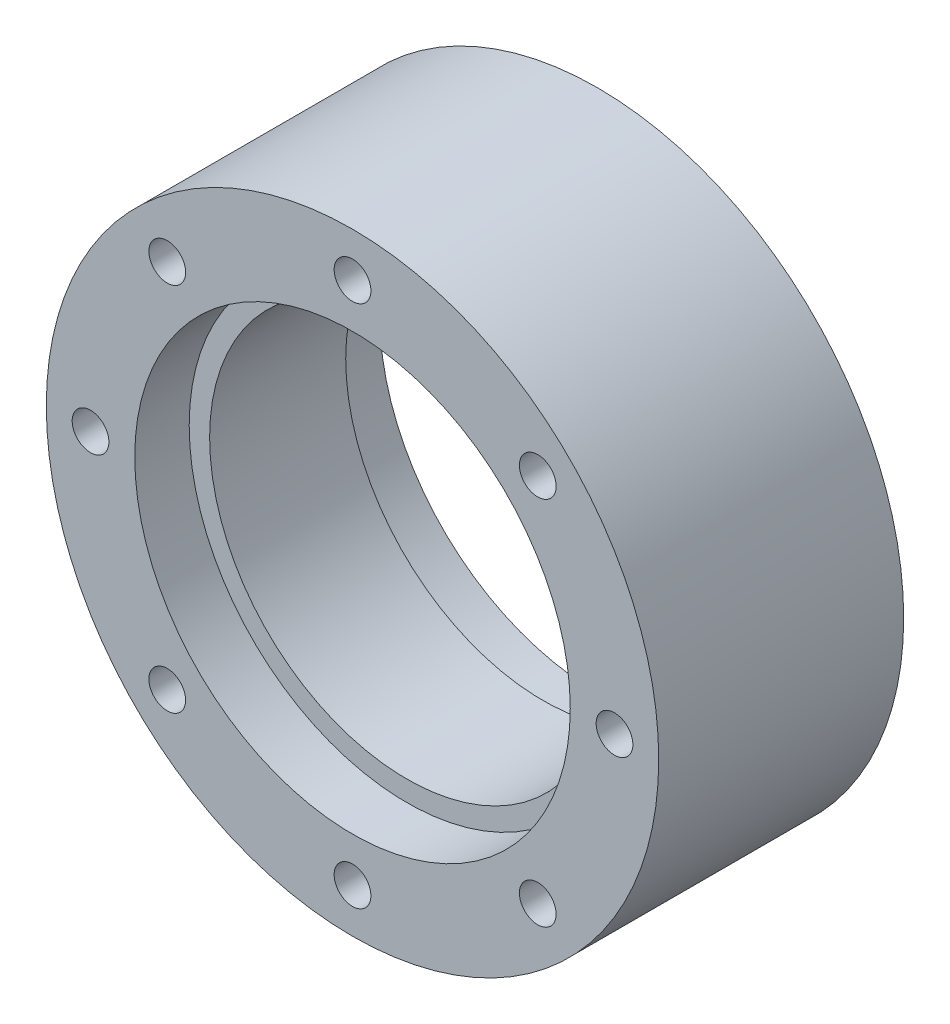
SolidWorks part; units mm, degrees
ref_plane "Front Plane" through (0, 0, 0) normal (0, 0, 1) x (1, 0, 0)
ref_plane "Top Plane" through (0, 0, 0) normal (0, 1, 0) x (1, 0, 0)
ref_plane "Right Plane" through (0, 0, 0) normal (1, 0, 0) x (0, 0, -1)
ref_axis "Z" through (0, 0, 9.9) along (0, 0, -1)
sketch "Sketch7" plane through (0, 0, 0) normal (0, 1, 0) x (1, 0, 0)
  line L0 (16, 9) -> (16, 5)
  line L2 (16, 5) -> (14.5, 5)
  line L5 (16, 9) -> (22.5, 9)
  line L6 (22.5, 9) -> (22.5, -9)
  line L7 (24.7452, 0) -> (-6.4078, 0) construction
  line L8 (16, -5) -> (14.5, -5)
  line L9 (16, -9) -> (16, -5)
  line L10 (14.5, 5) -> (14.5, -5)
  line L11 (22.5, -9) -> (16, -9)
  line L12 (0, -9.9) -> (0, 9.9) construction
  point P6 (0, 0)
  point P15 (19, 8.1756)
  point P16 (0, 0)
  dimension "D2" = 4
  dimension "D4" = 5
  dimension "D1" = 14.5
  dimension "D3" = 16
  dimension "D5" = 22.5
revolve "Revolve1" add sketch "Sketch7" angle 360 about axis through (0, 0, 9.9) along (0, 0, -1)
sketch "Sketch3" plane through (0, 0, 0) normal (0, 0, 1) x (1, 0, 0)
  line L0 (0, 0) -> (0, 19.25) construction
  circle A0 centre (0, 19.25) radius 1.35
  point P2 (-2.3677, 22.7393)
  point P4 (0, 0)
  dimension "D1" = 2.7
  dimension "D2" = 19.25
extrude "Cut-Extrude2" cut sketch "Sketch3" against normal through all both and the other way through all
sketch "Sketch4" plane through (0, 0, -9) normal (0, 0, -1) x (-1, 0, 0)
  circle A0 centre (0, 19.25) radius 2.25
  circle A1 centre (0, 19.25) radius 1.35 construction
  dimension "D1" = 4.5
extrude "Cut-Extrude4" cut sketch "Sketch4" against normal blind 2.5 and the other way through all
chamfer "Chamfer1" distance 0.1 angle 45 1 edges at (-1.35, 19.25, -6.5)
pattern_circular "CirPattern3" count 4 over 360 about axis through (0, 0, 0) along (0, 0, 1) of "Cut-Extrude4"
pattern_circular "CirPattern2" count 8 over 360 about axis through (0, 0, 0) along (0, 0, 1) of "Cut-Extrude2"
equation "\"BearingBaseDistance\"= 10"
equation "\"BearingOD\"= 32"
equation "\"BearingHeight\"= 4"
equation "\"SeatsOD\"= \"BearingOD\" + 10"
equation "\"WireHarnessHeight\"= 4"
equation "\"OuterWallWidth\"= 6"
equation "\"OverallOD\" = 45"
equation "\"BearingID\" = 25"
equation "\"OverallHeight\"= \"WireHarnessHeight\" + \"BearingHeight\"*2 + \"BearingBaseDistance\""
equation "\"RetainingRingThickness\" = 1.30"
equation "\"RetaininRingGrooveDiameter\" = 23.9"
equation "\"ShaftLengthAfterFlange\" = 2*\"BearingHeight\" + \"BearingBaseDistance\" + \"RetainingRingThickness\"*2\t'give a retaining ring thickness of extra clearance"
equation "\"RetainingRingGrooveBase\" = \"ShaftLengthAfterFlange\" - \"RetainingRingThickness\"*2"
equation "\"CoverThickness\" = 1"
equation "\"CoverClearance\" = 1"
equation "\"FlangHeight\" = 3"
equation "\"OuterHousingHeight\" = \"WireHarnessHeight\" + \"BearingHeight\"*2 + \"BearingBaseDistance\""
equation "\"PCBWidth\" = 5"
equation "\"PCBHeight\" = \"OuterHousingHeight\" "
equation "\"PCBThickness\" = 1"
equation "\"NormalDistSidewallPCBToZ\" = (\"OverallOD\"/2) - 1.6\t'radial distance from the z axis to pcb origin on the top/connector side"
equation "\"PCBSidewallCutoutClearance\" = 0.1"
equation "\"D3@Sketch7\"=\"BearingOD\"/2"
equation "\"D4@Sketch7\"=\"BearingBaseDistance\"/2"
equation "\"D5@Sketch7\"=\"OverallOD\"/2"
equation "\"D2@Sketch3\"=(\"OverallOD\"+\"BearingOD\")/4"
